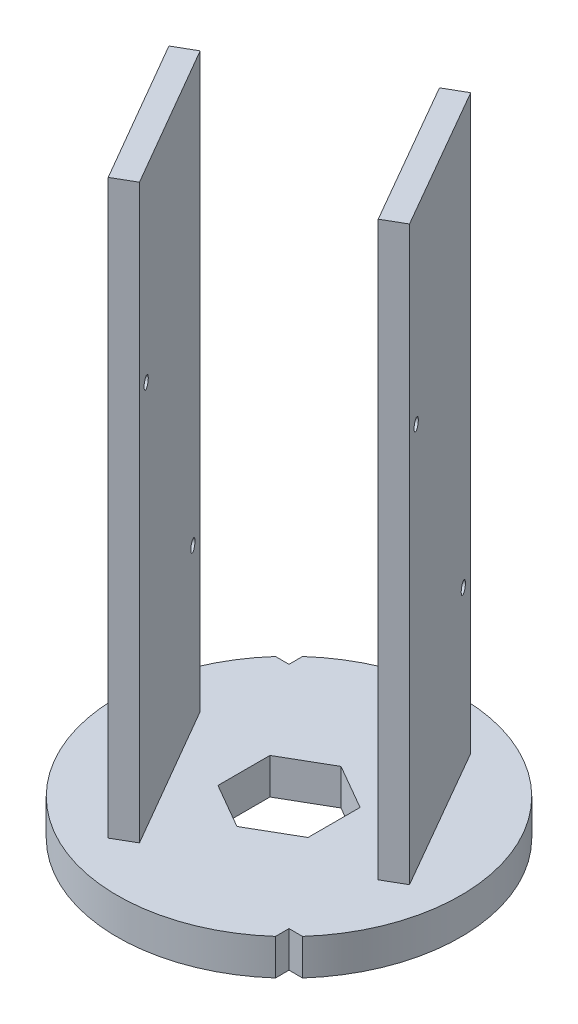
SolidWorks part; units mm, degrees
ref_plane "Front Plane" through (0, 0, 0) normal (0, 0, 1) x (1, 0, 0)
ref_plane "Top Plane" through (0, 0, 0) normal (0, 1, 0) x (1, 0, 0)
ref_plane "Right Plane" through (0, 0, 0) normal (1, 0, 0) x (0, 0, -1)
sketch "Sketch2" plane through (0, 0, 0) normal (0, 1, 0) x (1, 0, 0)
  line L0 (0, 0) -> (0, 38.1) construction
  line L1 (0, 11.547) -> (-10, 5.7735)
  line L2 (-10, 5.7735) -> (-10, -5.7735)
  line L3 (-10, -5.7735) -> (0, -11.547)
  line L4 (0, -11.547) -> (10, -5.7735)
  line L5 (10, -5.7735) -> (10, 5.7735)
  line L6 (10, 5.7735) -> (0, 11.547)
  line L7 (0, 0) -> (-38.1, 0) construction
  line L8 (0, 0) -> (38.1, 0) construction
  line L9 (0, 0) -> (0, -38.1) construction
  line L11 (-38.1, 0) -> (-25.4, 0)
  line L12 (-38.1, 0) -> (-38.1, 31.75)
  line L13 (-38.1, 31.75) -> (-25.4, 31.75)
  line L14 (-25.4, 0) -> (-25.4, 31.75)
  line L15 (0, 38.1) -> (-31.75, 38.1)
  line L16 (0, 38.1) -> (0, 25.4)
  line L17 (0, 25.4) -> (-31.75, 25.4)
  line L18 (-31.75, 38.1) -> (-31.75, 25.4)
  line L19 (38.1, 0) -> (25.4, 0)
  line L20 (38.1, 0) -> (38.1, -31.75)
  line L21 (38.1, -31.75) -> (25.4, -31.75)
  line L22 (25.4, 0) -> (25.4, -31.75)
  line L23 (0, -38.1) -> (31.75, -38.1)
  line L24 (0, -38.1) -> (0, -25.4)
  line L25 (0, -25.4) -> (31.75, -25.4)
  line L26 (31.75, -38.1) -> (31.75, -25.4)
  circle A0 centre (0, 0) radius 38.1
  circle A1 centre (0, 0) radius 10 construction
  dimension "D1" = 76.2
  dimension "D2" = 20
  dimension "D3" = 12.7
  dimension "D4" = 31.75
  dimension "D5" = 31.75
  dimension "D6" = 12.7
  dimension "D7" = 12.7
  dimension "D8" = 31.75
  dimension "D9" = 31.75
  dimension "D10" = 12.7
extrude "Boss-Extrude1" add sketch "Sketch2" along normal blind 8 contours L13 A0 L11 L14 | L16 A0 L18 L17 | L21 A0 L19 L22 | L24 A0 L26 L25 | L26 A0 L21 L22 L19 L16 L17 L18 L13 L14 L11 L24 L25 L6 L5 L4 L3 L2 L1
sketch "Sketch7" plane through (0, 8, 0) normal (0, 1, 0) x (1, 0, 0)
  line L0 (-20.2575, 7.7057) -> (-30.5728, 3.9138) construction
  line L1 (1.6846, 20.374) -> (-24.8988, 5.026) construction
  line L2 (-2.5209, -22.5726) -> (-12.0558, -28.0741) construction
  line L3 (-6.6939, -24.9819) -> (24.9819, -6.6939) construction
  line L4 (-30.5728, 3.9138) -> (-12.0558, -28.0741)
  line L5 (-30.5728, 3.9138) -> (-26.1763, 6.4588)
  line L6 (-12.0558, -28.0741) -> (-7.6593, -25.5291)
  line L7 (-26.1763, 6.4588) -> (-7.6593, -25.5291)
  dimension "D1" = 5.08
extrude "Boss-Extrude3" add sketch "Sketch7" along normal blind 127
ref_plane "Plane1" through (-21.7457, -1.979, -37.6647) normal (0.866, 0, -0.5) x (-0.5, 0, -0.866)
mirror "Mirror1" about plane through (-21.7457, -1.979, -37.6647) normal (0.866, 0, -0.5) of "Boss-Extrude3"
sketch "Sketch8" plane through (21.2304, 0, -12.225) normal (0.8666, 0, -0.499) x (-0.499, 0, -0.8666)
  line L0 (18.3098, 8.762) -> (-18.3098, 8.762) construction
  circle A0 centre (-14.2022, 93.725) radius 1.27
  circle A1 centre (14.2458, 42.925) radius 1.27
  dimension "D1" = 2.54
  dimension "D2" = 2.54
extrude "Cut-Extrude1" cut sketch "Sketch8" against normal blind 127
